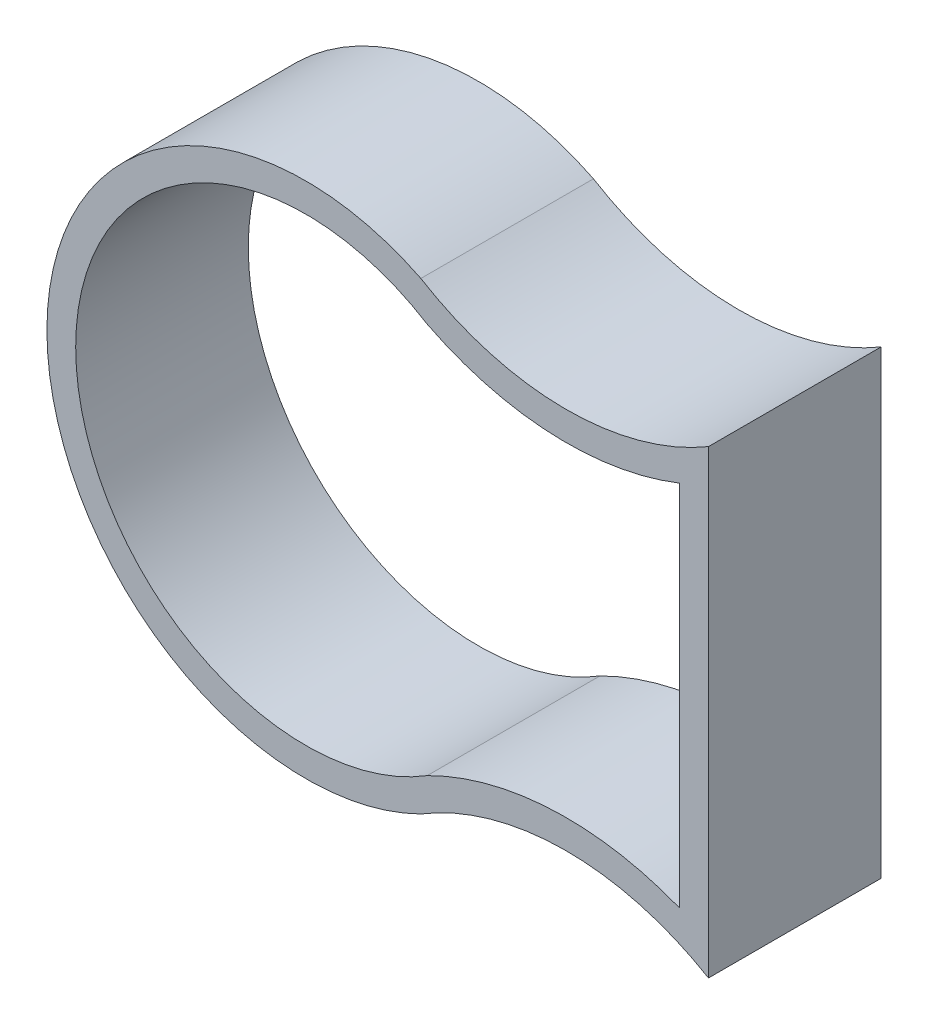
SolidWorks part; units mm, degrees
ref_plane "Front Plane" through (0, 0, 0) normal (0, 0, 1) x (1, 0, 0)
ref_plane "Top Plane" through (0, 0, 0) normal (0, 1, 0) x (1, 0, 0)
ref_plane "Right Plane" through (0, 0, 0) normal (1, 0, 0) x (0, 0, -1)
sketch "Sketch1" plane through (0, 0, 0) normal (0, 0, 1) x (1, 0, 0)
  line L0 (0, 0) -> (88.9, 0) construction
  line L1 (88.9, 50.8) -> (88.9, -50.8) construction
  line L2 (0, 57.15) -> (0, -57.15) construction
  line L3 (88.9, 50.8) -> (88.9, -50.8)
  line L4 (25.4, 51.1953) -> (25.4, -51.1953) construction
  line L5 (82.55, 40.6282) -> (82.55, -40.6282)
  circle A0 centre (0, 0) radius 57.15
  circle A1 centre (0, 0) radius 50.8
  arc A2 (25.4, 51.1953) -> (88.9, 50.8) centre (57.4786, 103.7862) ccw
  arc A3 (25.4, -51.1953) -> (88.9, -50.8) centre (57.4786, -103.7862) cw
  arc A4 (26.818, 43.1443) -> (82.55, 40.6282) centre (57.4786, 103.7862) ccw
  arc A5 (22.0933, -45.7742) -> (82.55, -40.6282) centre (57.4786, -103.7862) cw
  arc A6 (22.0933, 45.7742) -> (82.55, 40.6282) centre (57.4786, 103.7862) ccw construction
  dimension "D1" = 114.3
  dimension "D4" = 101.6
  dimension "D3" = 88.9
  dimension "D5" = 25.4
  dimension "D2" = 6.35
  dimension "D6" = 6.35
extrude "Boss-Extrude1" add sketch "Sketch1" along normal blind 38.1 contours A0 A3 L3 A2 | A0 A3 A2 A1
sketch3d "3DSketch1" plane through (0, 0, 0) normal (0, 0, 1) x (1, 0, 0)
  dimension "D1" = 71.12
